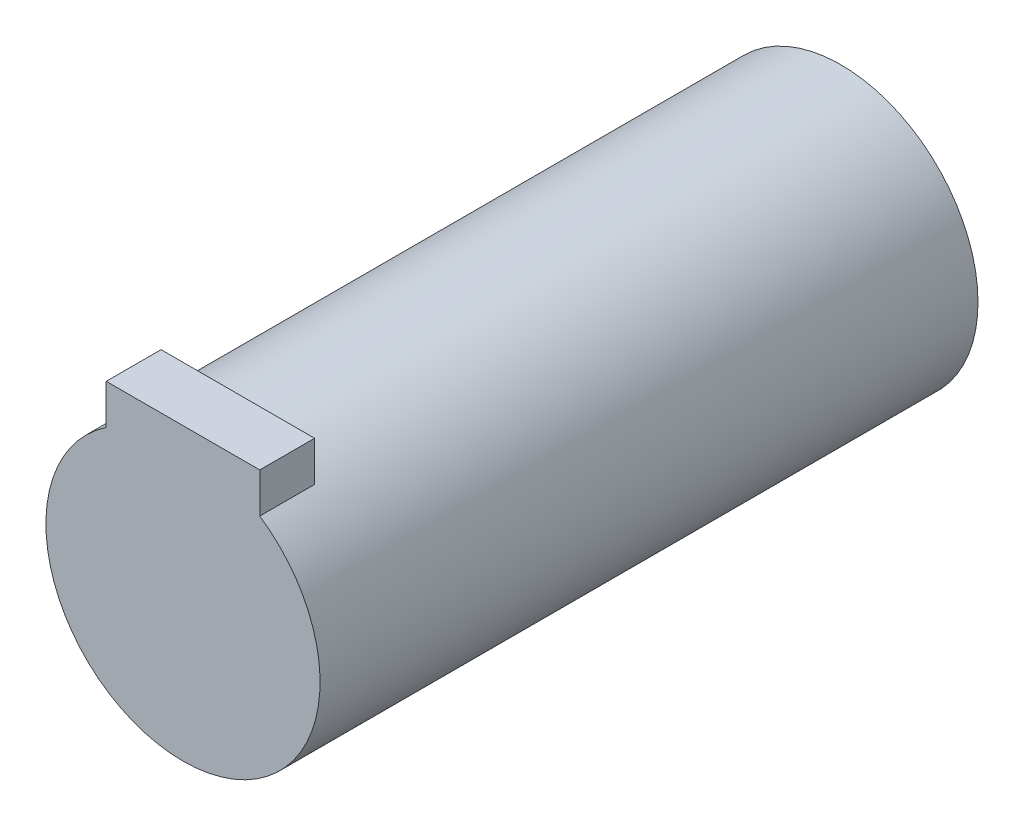
SolidWorks part; units mm, degrees
ref_plane "Alzado" through (0, 0, 0) normal (0, 0, 1) x (1, 0, 0)
ref_plane "Planta" through (0, 0, 0) normal (0, 1, 0) x (1, 0, 0)
ref_plane "Vista lateral" through (0, 0, 0) normal (1, 0, 0) x (0, 0, -1)
sketch "Sketch1" plane through (0, 0, 0) normal (0, 0, 1) x (1, 0, 0)
  circle A0 centre (0, 0) radius 12.5
  dimension "D1" = 25
extrude "Boss-Extrude1" add sketch "Sketch1" along normal blind 60
sketch "Sketch3" plane through (0, 0, 0) normal (0, 1, 0) x (1, 0, 0)
  line L1 (-7, -60) -> (7, -60)
  line L2 (-7, -60) -> (-7, -55)
  line L3 (-7, -55) -> (7, -55)
  line L4 (7, -60) -> (7, -55)
  line L5 (-12.5, -60) -> (12.5, -60) construction
  line L6 (-12.5, -60) -> (12.5, -60) construction
  point P5 (5.8142, -50.097)
  point P8 (0, -60)
  point P9 (0, -60)
  dimension "D1" = 5
  dimension "D2" = 14
extrude "Boss-Extrude2" add sketch "Sketch3" along normal blind 14
